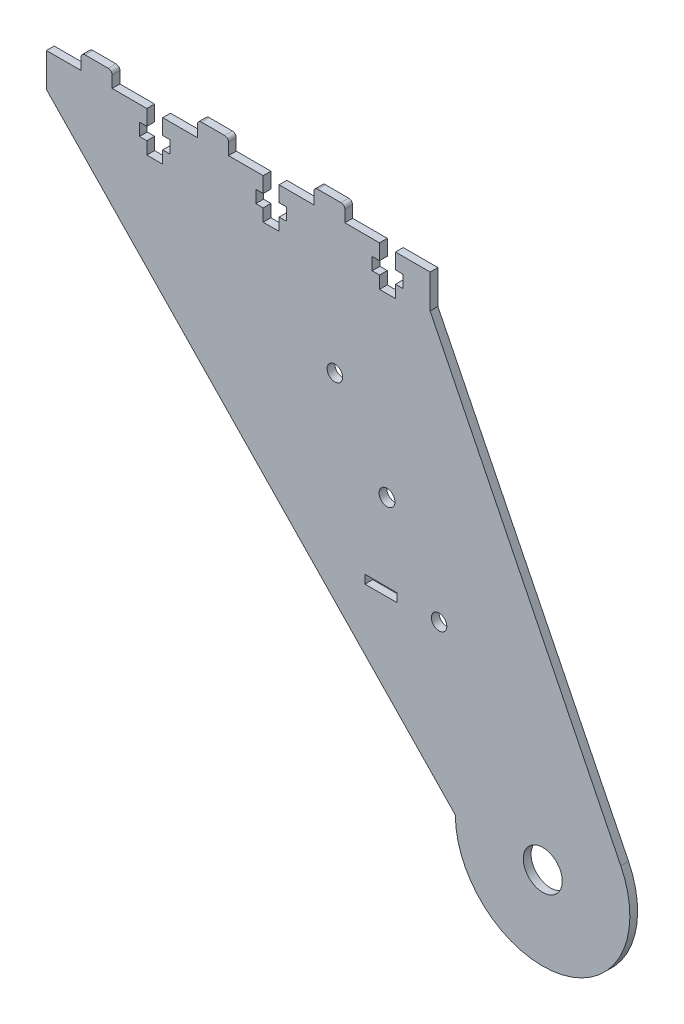
SolidWorks part; units mm, degrees
ref_plane "前视基准面" through (0, 0, 0) normal (0, 0, 1) x (1, 0, 0)
ref_plane "上视基准面" through (0, 0, 0) normal (0, 1, 0) x (1, 0, 0)
ref_plane "右视基准面" through (0, 0, 0) normal (1, 0, 0) x (0, 0, -1)
sketch "草图1" plane through (0, 0, 0) normal (0, 0, 1) x (1, 0, 0)
  line L0 (-19.7627, 31.422) -> (7.0984, -10.75) construction
  line L2 (-36.2, 68.25) -> (-36.2, 58.15) construction
  line L15 (-38.25, 66.25) -> (-38.25, 62.25)
  line L16 (-38.25, 62.25) -> (-40.15, 62.25)
  line L17 (-40.15, 62.25) -> (-40.15, 59.05)
  line L18 (-40.15, 59.05) -> (-38.25, 59.05)
  line L19 (-38.25, 59.05) -> (-38.25, 55.85)
  line L20 (-38.25, 55.85) -> (-34.15, 55.85)
  line L21 (-38.25, 66.25) -> (-47.2, 66.25)
  line L22 (-51.2, 66.25) -> (-51.2, 70.25) construction
  line L23 (-47.2, 66.25) -> (-55.2, 66.25) construction
  line L24 (-47.2, 66.25) -> (-47.2, 70.25)
  line L25 (-47.2, 70.25) -> (-55.2, 70.25)
  line L26 (-55.2, 66.25) -> (-55.2, 70.25)
  line L27 (-25.2, 66.25) -> (-17.2, 66.25) construction
  line L28 (-21.2, 66.25) -> (-21.2, 70.25) construction
  line L29 (-17.2, 66.25) -> (-17.2, 70.25)
  line L30 (-25.2, 70.25) -> (-17.2, 70.25)
  line L31 (-25.2, 66.25) -> (-25.2, 70.25)
  line L32 (-34.15, 66.25) -> (-25.2, 66.25)
  line L33 (-34.15, 59.05) -> (-34.15, 55.85)
  line L34 (-32.25, 59.05) -> (-34.15, 59.05)
  line L35 (-32.25, 62.25) -> (-32.25, 59.05)
  line L36 (-34.15, 62.25) -> (-32.25, 62.25)
  line L37 (-34.15, 66.25) -> (-34.15, 62.25)
  line L38 (-94.15, 66.25) -> (-94.15, 57.55)
  line L39 (-94.15, 57.55) -> (11.3, -51.75)
  line L40 (-68.25, 66.25) -> (-68.25, 62.25)
  line L41 (-68.25, 62.25) -> (-70.15, 62.25)
  line L42 (-70.15, 62.25) -> (-70.15, 59.05)
  line L43 (-70.15, 59.05) -> (-68.25, 59.05)
  line L44 (-68.25, 59.05) -> (-68.25, 55.85)
  line L45 (-68.25, 66.25) -> (-77.2, 66.25)
  line L46 (-6.2, 68.25) -> (-6.2, 58.15) construction
  line L49 (-64.15, 55.85) -> (-68.25, 55.85)
  line L50 (-64.15, 59.05) -> (-64.15, 55.85)
  line L51 (-62.25, 59.05) -> (-64.15, 59.05)
  line L52 (-62.25, 62.25) -> (-62.25, 59.05)
  line L53 (-64.15, 62.25) -> (-62.25, 62.25)
  line L54 (-64.15, 66.25) -> (-64.15, 62.25)
  line L55 (-55.2, 66.25) -> (-64.15, 66.25)
  line L58 (-8.25, 66.25) -> (-17.2, 66.25)
  line L59 (-94.15, 66.25) -> (-85.2, 66.25)
  line L60 (-85.2, 66.25) -> (-85.2, 70.25)
  line L61 (-77.2, 70.25) -> (-85.2, 70.25)
  line L62 (-77.2, 66.25) -> (-77.2, 70.25)
  line L63 (4.8, 66.25) -> (4.8, 57.55)
  line L65 (7.0984, -10.75) -> (-7.9016, -10.75) construction
  line L66 (-8.25, 66.25) -> (-8.25, 62.25)
  line L67 (-8.25, 62.25) -> (-10.15, 62.25)
  line L68 (-10.15, 62.25) -> (-10.15, 59.05)
  line L69 (-10.15, 59.05) -> (-8.25, 59.05)
  line L70 (-8.25, 59.05) -> (-8.25, 55.85)
  line L74 (-4.15, 66.25) -> (4.8, 66.25)
  line L75 (-4.15, 55.85) -> (-8.25, 55.85)
  line L76 (-4.15, 59.05) -> (-4.15, 55.85)
  line L77 (-2.25, 59.05) -> (-4.15, 59.05)
  line L78 (-2.25, 62.25) -> (-2.25, 59.05)
  line L79 (-4.15, 62.25) -> (-2.25, 62.25)
  line L80 (-4.15, 66.25) -> (-4.15, 62.25)
  line L86 (4.8, 57.55) -> (53.9646, -41.7681)
  line L87 (-12.0016, -11.85) -> (-3.8016, -11.85)
  line L88 (-12.0016, -11.85) -> (-12.0016, -9.65)
  line L89 (-12.0016, -9.65) -> (-3.8016, -9.65)
  line L90 (-3.8016, -11.85) -> (-3.8016, -9.65)
  line L91 (-12.0016, -11.85) -> (-3.8016, -9.65) construction
  line L92 (-12.0016, -9.65) -> (-3.8016, -11.85) construction
  circle A0 centre (-36.2, 68.25) radius 2.05 construction
  circle A1 centre (-19.7627, 31.422) radius 2
  circle A2 centre (7.0984, -10.75) radius 2
  circle A3 centre (33.8, -51.75) radius 22.5 construction
  arc A6 (11.3, -51.75) -> (53.9646, -41.7681) centre (33.8, -51.75) ccw
  circle A7 centre (33.85, -52.75) radius 5.02
  circle A8 centre (-6.3322, 10.336) radius 2.05
  point P39 (-36.2, 55.85)
  point P61 (-66.2, 55.85)
  point P91 (-6.2, 55.85)
  dimension "D17" = 10.04
  dimension "D20" = 4
  dimension "D12" = 4.1
  dimension "D5" = 4
  dimension "D6" = 2
  dimension "D7" = 3.2
  dimension "D8" = 3.2
  dimension "D9" = 15
  dimension "D10" = 8
  dimension "D11" = 4
  dimension "D13" = 8.2
  dimension "D14" = 2.2
  dimension "D15" = 10.1
  dimension "D16" = 15
extrude "凸台-拉伸1" add sketch "草图1" along normal blind 2
sketch "草图2" plane through (0, 66.25, 0) normal (0, 1, 0) x (1, 0, 0)
  line L0 (-8.25, -1) -> (-4.15, -1)
  line L1 (-8.25, -2) -> (-8.25, 0) construction
  line L2 (-4.15, -2) -> (-4.15, 0) construction
  circle A0 centre (-6.2, -1) radius 2.05
fillet "圆角1" radius 1 6 edges at (-17.2, 70.25, 1) (-25.2, 70.25, 1) (-47.2, 70.25, 1) (-55.2, 70.25, 1) (-77.2, 70.25, 1) (-85.2, 70.25, 1)
